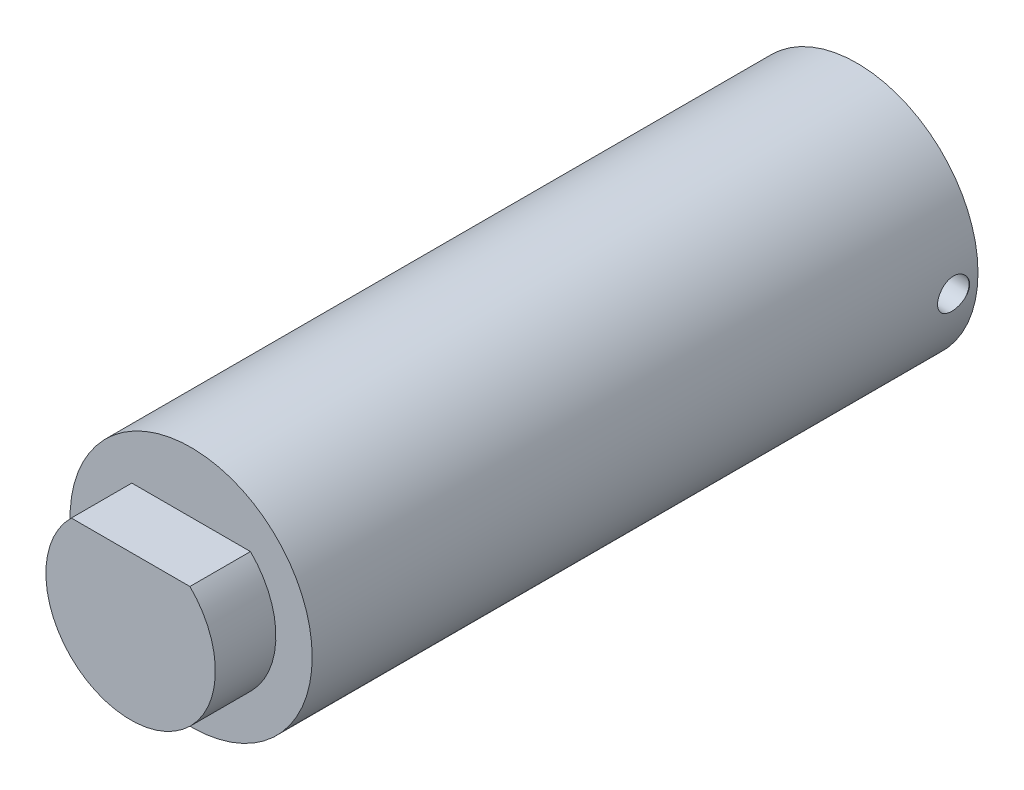
SolidWorks part; units mm, degrees
ref_plane "Plano frontal" through (0, 0, 0) normal (0, 0, 1) x (1, 0, 0)
ref_plane "Plano superior" through (0, 0, 0) normal (0, 1, 0) x (1, 0, 0)
ref_plane "Plano direito" through (0, 0, 0) normal (1, 0, 0) x (0, 0, -1)
sketch "Esboço1" plane through (0, 0, 0) normal (0, 0, 1) x (1, 0, 0)
  circle A0 centre (0, 0) radius 10
  dimension "D1" = 20
extrude "Ressalto-extrusão1" add sketch "Esboço1" along normal blind 60
sketch "Esboço7" plane through (0, 0, 60) normal (0, 0, 1) x (1, 0, 0)
  circle A0 centre (0, 0) radius 7
  circle A1 centre (0, 0) radius 10 construction
  circle A2 centre (0, 0) radius 10
  dimension "D1" = 3
extrude "Corte-extrusão1" cut sketch "Esboço7" against normal blind 5
sketch "Esboço9" plane through (0, 0, 60) normal (0, 0, 1) x (1, 0, 0)
  line L0 (-4.899, 5) -> (4.899, 5)
  circle A0 centre (0, 0) radius 7 construction
  arc A1 (4.899, 5) -> (-4.899, 5) centre (0, 0) ccw
  circle A2 centre (0, 0) radius 7 construction
  point P9 (0, 0)
  point P10 (0, 0)
  dimension "D1" = 5
extrude "Corte-extrusão2" cut sketch "Esboço9" against normal blind 5
hole_wizard "Furo com folga de M21" positions "3DSketch5" profile "Esboço15" hole size "M2" standard "ISO" end condition through all
sketch3d "3DSketch5"
  line L0 (9.9845, -0.5558, 0) -> (9.9845, -0.5558, 55) construction
  circle A0 centre (0, 0, 0) radius 10 construction
  circle A1 centre (0, 0, 55) radius 10 construction
  point P0 (9.9845, -0.5558, 2)
  point P7 (0, 0, 10)
  point P10 (0, 0, 65)
  point P12 (9.8567, 1.6867, 5.0337)
  dimension "D1" = 2
sketch "Esboço15" plane through (9.9845, -0.5558, 2) normal (0, 0, 1) x (0.0556, 0.9985, 0)
  line L0 (0, 0) -> (0, 20.5403)
  line L1 (0, 20.5403) -> (1.3, 20.5403)
  line L2 (1.3, 20.5403) -> (1.3, 0.025)
  line L3 (1.3, 0.025) -> (1.325, 0)
  line L5 (1.325, 0) -> (0, 0)
  line L6 (-1.3, 0.025) -> (-1.325, 0) construction
  line L11 (0, -6.35) -> (0, 107.95) construction
  dimension "Thru Hole Dia." = 2.6
  dimension "Thru Hole Depth" = 20.5403
  dimension "Near C'Sink Dia." = 2.65
  dimension "Near C'Sink Angle" = 90
